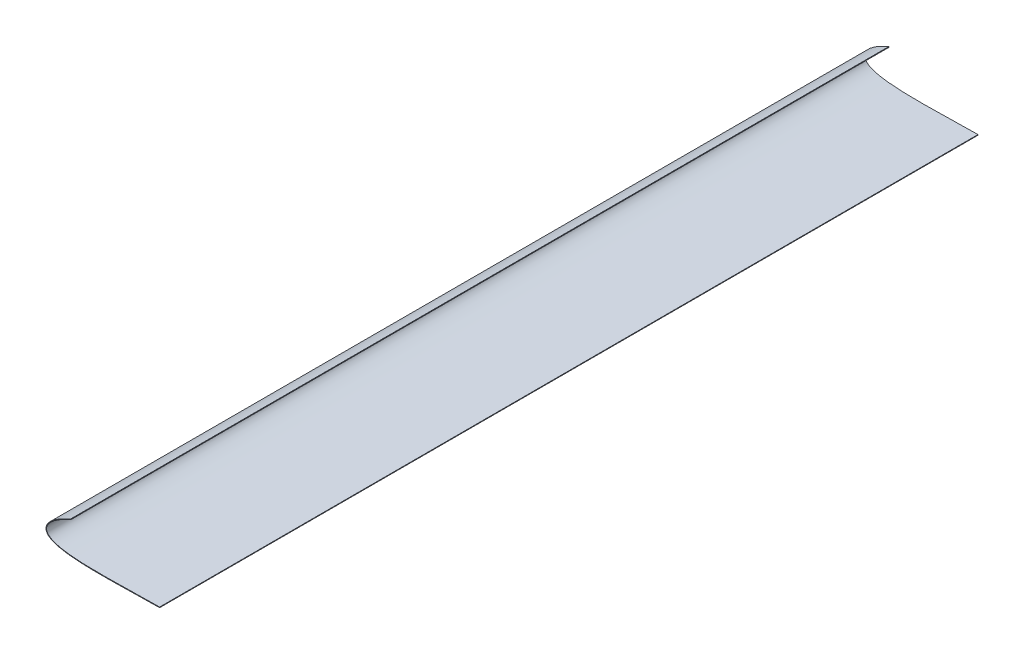
SolidWorks part; units mm, degrees
ref_plane "Front Plane" through (0, 0, 0) normal (0, 0, 1) x (1, 0, 0)
ref_plane "Top Plane" through (0, 0, 0) normal (0, 1, 0) x (1, 0, 0)
ref_plane "Right Plane" through (0, 0, 0) normal (1, 0, 0) x (0, 0, -1)
curve "ImportedCurve1"
curve "ImportedCurve2"
curve "ImportedCurve3"
curve "ImportedCurve4"
sketch "Sketch2" plane through (0, 0, 0) normal (0, 0, 1) x (1, 0, 0)
  line L0 (52.451, 54.1567) -> (52.2798, 54.6368) construction
  line L1 (130.5487, 26.5347) -> (130.5552, 26.0143) construction
  line L2 (52.451, 54.1567) -> (52.2798, 54.6368)
  line L3 (130.5487, 26.5347) -> (130.5552, 26.0143)
  spline S0 degree 3 poles (-609.5106, 1939.9204) (156.5302, 48.5797) (93.2015, 73.7291) (48.7263, 53.0365) (46.1986, 51.7856) (43.8514, 50.5628) (41.7065, 49.2754) (39.7334, 48.0293) (37.966, 46.7509) (36.3543, 45.5543) (34.9506, 44.3247) (33.731, 43.1376) (32.6875, 41.9647) (31.87, 40.7951) (31.2049, 39.6569) (30.8086, 38.5196) (30.5236, 37.4345) (30.431, 36.3628) (30.615, 35.3293) (30.8928, 34.3178) (31.4496, 33.3932) (32.1507, 32.5234) (32.9767, 31.6506) (34.0717, 30.9441) (35.2743, 30.2147) (36.6607, 29.5586) (38.2299, 28.9796) (39.9603, 28.4092) (41.8621, 27.9077) (43.9308, 27.4768) (46.1431, 27.0545) (48.5261, 26.7119) (51.0446, 26.3949) (53.7227, 26.0665) (56.5512, 25.9162) (59.5208, 25.6697) (62.6353, 25.5643) (65.8829, 25.3781) (69.2727, 25.3117) (72.7876, 25.2447) (76.441, 25.2178) (80.208, 25.2059) (84.0996, 25.2543) (88.0934, 25.2344) (92.2095, 25.3673) (96.4279, 25.3705) (100.7574, 25.4491) (105.1745, 25.5547) (109.6916, 25.6471) (114.2949, 25.7362) (118.9982, 25.8022) (123.7865, 25.9376) (322.7856, 28.0491) (519.4346, 57.8552) (821.0751, -1819.4277) knots 8.608586 8.608586 8.608586 8.608586 14.172368 14.290637 14.400564 14.505491 14.603093 14.69595 14.781007 14.860667 14.932933 15.001195 15.06164 15.117978 15.169576 15.216705 15.259669 15.302009 15.342391 15.383062 15.425175 15.468584 15.515144 15.566223 15.621722 15.681368 15.746954 15.819191 15.896502 15.979092 16.068737 16.162461 16.263371 16.368582 16.481002 16.597802 16.720476 16.84899 16.981978 17.12087 17.264218 17.413488 17.565777 17.723889 17.885151 18.052109 18.222097 18.396578 18.573966 18.755717 18.940377 19.12953 19.321463 42.444936 42.444936 42.444936 42.444936 only from (52.2798, 54.6368) to (130.5552, 26.0143) construction
  spline S1 degree 3 poles (-783.0609, 1855.4535) (449.5688, -93.7685) (190.7468, 114.8682) (48.5985, 52.4662) (45.1489, 50.7908) (39.5693, 47.3621) (37.2938, 45.7687) (33.6489, 42.4218) (32.1506, 40.6939) (30.974, 37.4872) (30.8417, 36.1863) (31.6369, 33.8106) (32.4947, 32.7613) (34.3648, 31.279) (35.3859, 30.7214) (37.4227, 29.7823) (38.5093, 29.4116) (41.8889, 28.3539) (44.2531, 27.8939) (49.0056, 27.1184) (51.4047, 26.8526) (58.6332, 26.2111) (63.4698, 25.9577) (73.1544, 25.7277) (77.9969, 25.7165) (92.7642, 25.8004) (102.664, 26.0308) (289.6368, 29.3648) (467.9511, 56.9541) (643.2169, -1883.5642) knots -3.826981 -3.826981 -3.826981 -3.826981 14.151211 14.151211 14.604184 14.604184 14.932416 14.932416 15.199765 15.199765 15.362932 15.362932 15.5261 15.5261 15.66286 15.66286 15.79962 15.79962 16.086125 16.086125 16.37263 16.37263 16.945639 16.945639 17.518648 17.518648 18.689255 18.689255 39.607575 39.607575 39.607575 39.607575 only from (52.451, 54.1567) to (130.5487, 26.5347) construction
  spline S2 degree 3 poles (52.2798, 54.6368) (51.9842, 54.5111) (50.7699, 53.9873) (48.7263, 53.0365) (46.1986, 51.7856) (43.8514, 50.5628) (41.7065, 49.2754) (39.7334, 48.0293) (37.966, 46.7509) (36.3543, 45.5543) (34.9506, 44.3247) (33.731, 43.1376) (32.6875, 41.9647) (31.87, 40.7951) (31.2049, 39.6569) (30.8086, 38.5196) (30.5236, 37.4345) (30.431, 36.3628) (30.615, 35.3293) (30.8928, 34.3178) (31.4496, 33.3932) (32.1507, 32.5234) (32.9767, 31.6506) (34.0717, 30.9441) (35.2743, 30.2147) (36.6607, 29.5586) (38.2299, 28.9796) (39.9603, 28.4092) (41.8621, 27.9077) (43.9308, 27.4768) (46.1431, 27.0545) (48.5261, 26.7119) (51.0446, 26.3949) (53.7227, 26.0665) (56.5512, 25.9162) (59.5208, 25.6697) (62.6353, 25.5643) (65.8829, 25.3781) (69.2727, 25.3117) (72.7876, 25.2447) (76.441, 25.2178) (80.208, 25.2059) (84.0996, 25.2543) (88.0934, 25.2344) (92.2095, 25.3673) (96.4279, 25.3705) (100.7574, 25.4491) (105.1745, 25.5547) (109.6916, 25.6471) (114.2949, 25.7362) (118.9982, 25.8022) (123.7865, 25.9376) (127.6521, 25.9786) (129.9161, 26.0063) (130.5552, 26.0143) knots 14.134429 14.134429 14.134429 14.134429 14.172368 14.290637 14.400564 14.505491 14.603093 14.69595 14.781007 14.860667 14.932933 15.001195 15.06164 15.117978 15.169576 15.216705 15.259669 15.302009 15.342391 15.383062 15.425175 15.468584 15.515144 15.566223 15.621722 15.681368 15.746954 15.819191 15.896502 15.979092 16.068737 16.162461 16.263371 16.368582 16.481002 16.597802 16.720476 16.84899 16.981978 17.12087 17.264218 17.413488 17.565777 17.723889 17.885151 18.052109 18.222097 18.396578 18.573966 18.755717 18.940377 19.12953 19.321463 19.396956 19.396956 19.396956 19.396956
  spline S3 degree 3 poles (52.451, 54.1567) (52.3312, 54.1046) (52.2116, 54.0523) (48.5985, 52.4662) (45.1489, 50.7908) (39.5693, 47.3621) (37.2938, 45.7687) (33.6489, 42.4218) (32.1506, 40.6939) (30.974, 37.4872) (30.8417, 36.1863) (31.6369, 33.8106) (32.4947, 32.7613) (34.3648, 31.279) (35.3859, 30.7214) (37.4227, 29.7823) (38.5093, 29.4116) (41.8889, 28.3539) (44.2531, 27.8939) (49.0056, 27.1184) (51.4047, 26.8526) (58.6332, 26.2111) (63.4698, 25.9577) (73.1544, 25.7277) (77.9969, 25.7165) (92.7642, 25.8004) (102.664, 26.0308) (118.5633, 26.3143) (124.5553, 26.4491) (130.5487, 26.5347) knots 14.135709 14.135709 14.135709 14.135709 14.151211 14.151211 14.604184 14.604184 14.932416 14.932416 15.199765 15.199765 15.362932 15.362932 15.5261 15.5261 15.66286 15.66286 15.79962 15.79962 16.086125 16.086125 16.37263 16.37263 16.945639 16.945639 17.518648 17.518648 18.689255 18.689255 19.396987 19.396987 19.396987 19.396987
extrude "Boss-Extrude1" add sketch "Sketch2" along normal blind 720.725
